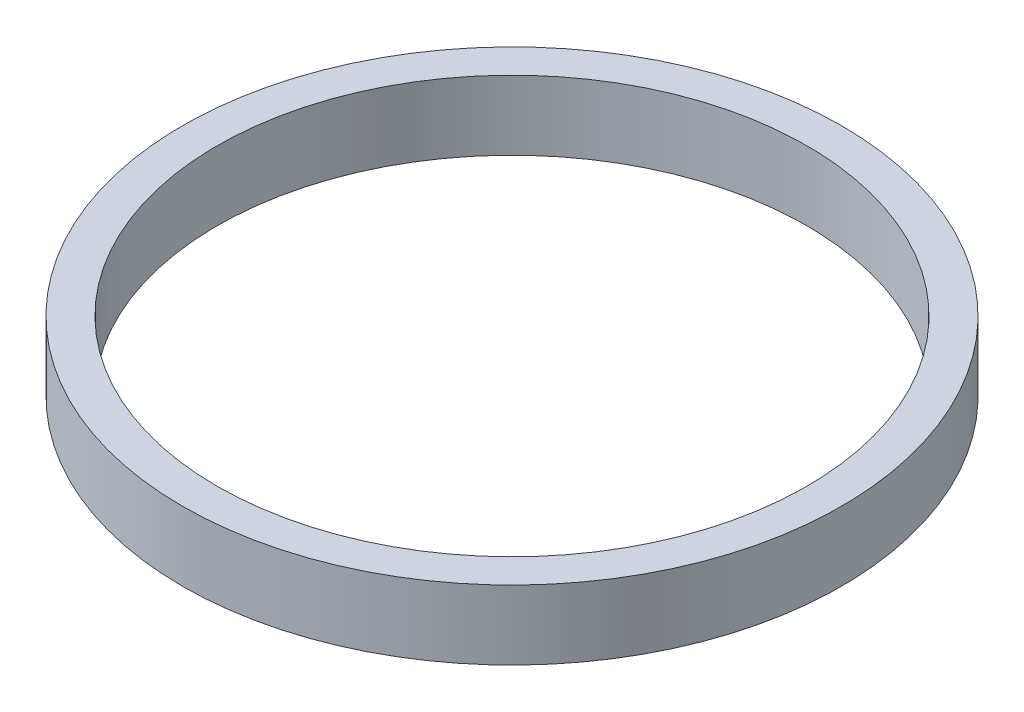
SolidWorks part; units mm, degrees
ref_plane "Front Plane" through (0, 0, 0) normal (0, 0, 1) x (1, 0, 0)
ref_plane "Top Plane" through (0, 0, 0) normal (0, 1, 0) x (1, 0, 0)
ref_plane "Right Plane" through (0, 0, 0) normal (1, 0, 0) x (0, 0, -1)
sketch "Sketch1" plane through (0, 0, 0) normal (0, 1, 0) x (1, 0, 0)
  circle A0 centre (0, 0) radius 42.55
  circle A1 centre (0, 0) radius 47.55
  dimension "D1" = 85.1
  dimension "D2" = 95.1
extrude "Boss-Extrude1" add sketch "Sketch1" along normal blind 10
